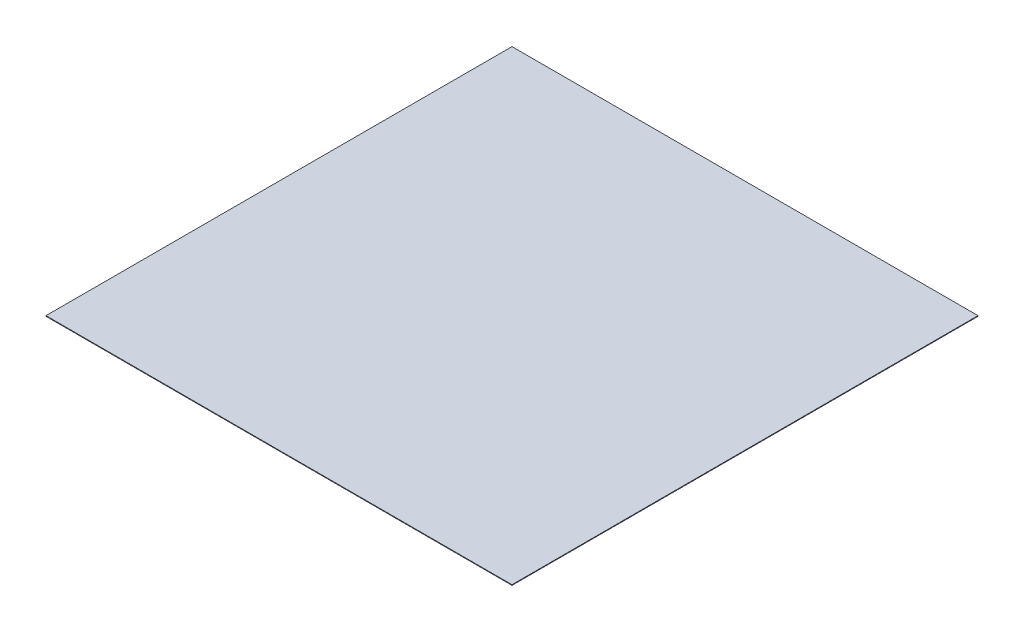
SolidWorks part; units mm, degrees
material "Corrugated Paper"
ref_plane "Front Plane" through (0, 0, 0) normal (0, 0, 1) x (1, 0, 0)
ref_plane "Top Plane" through (0, 0, 0) normal (0, 1, 0) x (1, 0, 0)
ref_plane "Right Plane" through (0, 0, 0) normal (1, 0, 0) x (0, 0, -1)
sketch "Sketch1" plane through (0, 0, 0) normal (0, 1, 0) x (1, 0, 0)
  line L1 (0, 0) -> (76.2, 0)
  line L2 (0, 0) -> (0, 76.2)
  line L3 (0, 76.2) -> (76.2, 76.2)
  line L4 (76.2, 0) -> (76.2, 76.2)
  dimension "D1" = 76.2
  dimension "D2" = 76.2
extrude "Boss-Extrude1" add sketch "Sketch1" along normal blind 0.1016
